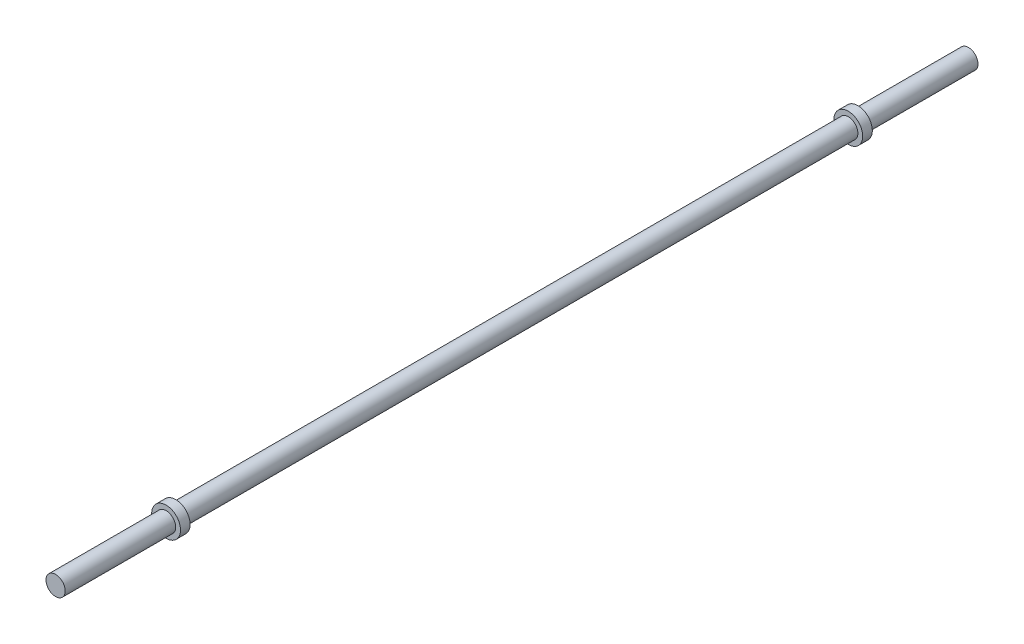
SolidWorks part; units mm, degrees
ref_plane "Front Plane" through (0, 0, 0) normal (0, 0, 1) x (1, 0, 0)
ref_plane "Top Plane" through (0, 0, 0) normal (0, 1, 0) x (1, 0, 0)
ref_plane "Right Plane" through (0, 0, 0) normal (1, 0, 0) x (0, 0, -1)
sketch "Sketch2" plane through (0, 0, 0) normal (0, 0, 1) x (1, 0, 0)
  circle A0 centre (0, 0) radius 1
  dimension "D1" = 2
extrude "Boss-Extrude1" add sketch "Sketch2" against normal blind 95
sketch "Sketch3" plane through (0, 0, 0) normal (0, 0, 1) x (1, 0, 0)
  circle A0 centre (0, 0) radius 1.5
  dimension "D1" = 3
extrude "Boss-Extrude2" add sketch "Sketch3" along normal blind 1 from offset 12.5 contours A0 offset against normal yes
sketch "Sketch4" plane through (0, 0, -95) normal (0, 0, -1) x (-1, 0, 0)
  circle A0 centre (0, 0) radius 1.5
  dimension "D1" = 3
extrude "Boss-Extrude3" add sketch "Sketch4" along normal blind 1 from offset 12.5
